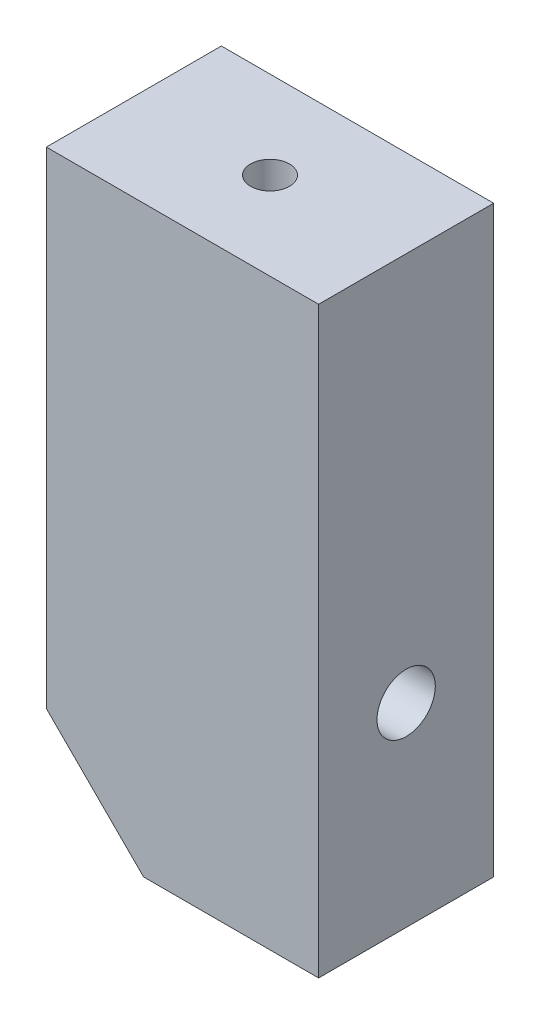
SolidWorks part; units mm, degrees
ref_plane "Front Plane" through (0, 0, 0) normal (0, 0, 1) x (1, 0, 0)
ref_plane "Top Plane" through (0, 0, 0) normal (0, 1, 0) x (1, 0, 0)
ref_plane "Right Plane" through (0, 0, 0) normal (1, 0, 0) x (0, 0, -1)
sketch "Sketch1" plane through (0, 0, 0) normal (0, 0, 1) x (1, 0, 0)
  line L1 (-14, 30) -> (14, 30)
  line L2 (-14, 30) -> (-14, -30)
  line L3 (-14, -30) -> (14, -30)
  line L4 (14, 30) -> (14, -30)
  line L5 (-14, 30) -> (14, -30) construction
  line L6 (-14, -30) -> (14, 30) construction
  point P0 (0, 0)
  dimension "D1" = 60
  dimension "D2" = 28
extrude "Boss-Extrude1" add sketch "Sketch1" along normal blind 18
chamfer "Chamfer1" distance 10 angle 45 1 edges at (-14, -30, 9)
hole_wizard "Ø4.0 (4) Diameter Hole1" positions "Sketch3" profile "Sketch2" hole size "Ø4.0" standard "ISO"
sketch "Sketch3" plane through (0, 30, 0) normal (0, 1, 0) x (1, 0, 0)
  point P0 (0, -9)
sketch "Sketch2" plane through (0, 30, 9) normal (1, 0, 0) x (0, 0, 1)
  line L0 (0, 0) -> (0, 31.2017)
  line L1 (0, 31.2017) -> (2, 30)
  line L2 (2, 30) -> (2, 0)
  line L5 (2, 0) -> (0, 0)
  line L10 (0, 31.2017) -> (-2, 30) construction
  line L11 (0, -6.35) -> (0, 107.95) construction
  dimension "Hole Dia." = 4
  dimension "Hole Depth" = 30
  dimension "Drill Angle" = 118
hole_wizard "Ø6.0 (6) Diameter Hole2" positions "Sketch11" profile "Sketch10" hole size "Ø6.0" standard "ISO"
sketch "Sketch11" plane through (14, 0, 0) normal (1, 0, 0) x (0, 0, -1)
  point P0 (-9, -10)
sketch "Sketch10" plane through (14, -10, 9) normal (0, 1, 0) x (0, 0, -1)
  line L0 (0, 0) -> (0, 18)
  line L1 (0, 18) -> (3, 18)
  line L2 (3, 18) -> (3, 0)
  line L5 (3, 0) -> (0, 0)
  line L10 (0, 18) -> (-3, 18) construction
  line L11 (0, -6.35) -> (0, 107.95) construction
  dimension "Hole Dia." = 6
  dimension "Hole Depth" = 18
  dimension "Drill Angle" = 180
